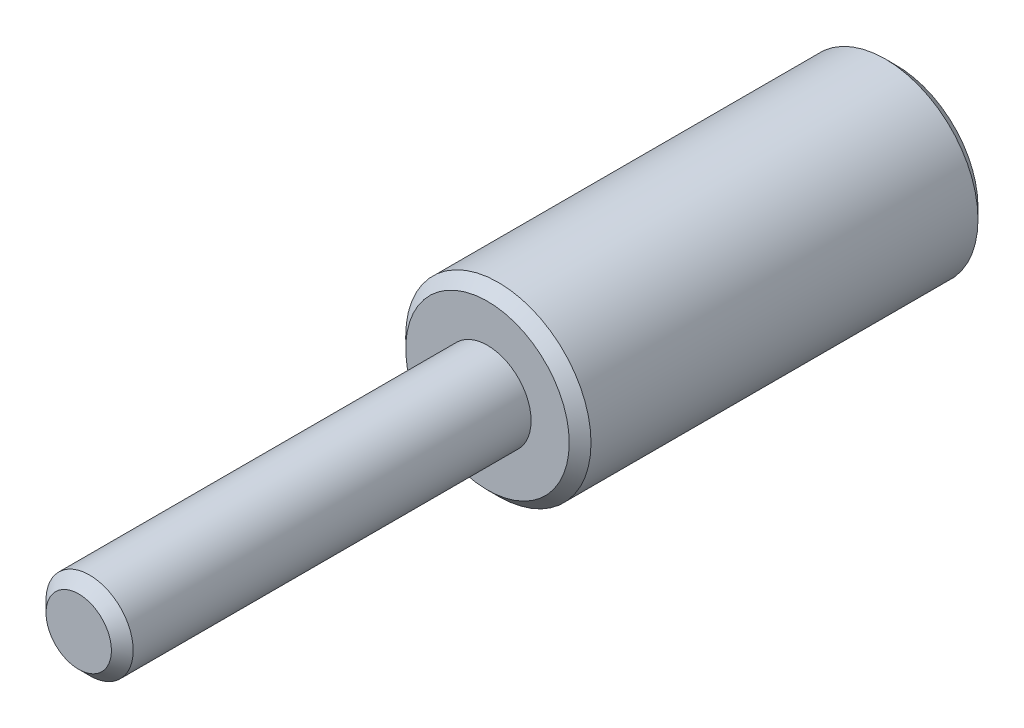
SolidWorks part; units mm, degrees
material "1.7045 (42Cr4)"
ref_plane "Спереди" through (0, 0, 0) normal (0, 0, 1) x (1, 0, 0)
ref_plane "Сверху" through (0, 0, 0) normal (0, 1, 0) x (1, 0, 0)
ref_plane "Справа" through (0, 0, 0) normal (1, 0, 0) x (0, 0, -1)
sketch "Эскиз1" plane through (0, 0, 0) normal (0, 0, 1) x (1, 0, 0)
  circle A0 centre (0, 0) radius 17
extrude "Бобышка-Вытянуть1" add sketch "Эскиз1" along normal blind 75
sketch "Эскиз2" plane through (0, 0, 75) normal (0, 0, 1) x (1, 0, 0)
  circle A0 centre (0, 0) radius 8
extrude "Бобышка-Вытянуть2" add sketch "Эскиз2" along normal blind 75
chamfer "Фаска1" distance 2 1 edges at (8, 0, 150)
chamfer "Фаска2" distance 2 angle 45 1 edges at (17, 0, 75)
chamfer "Фаска3" distance 2 angle 45 1 edges at (17, 0, 0)
